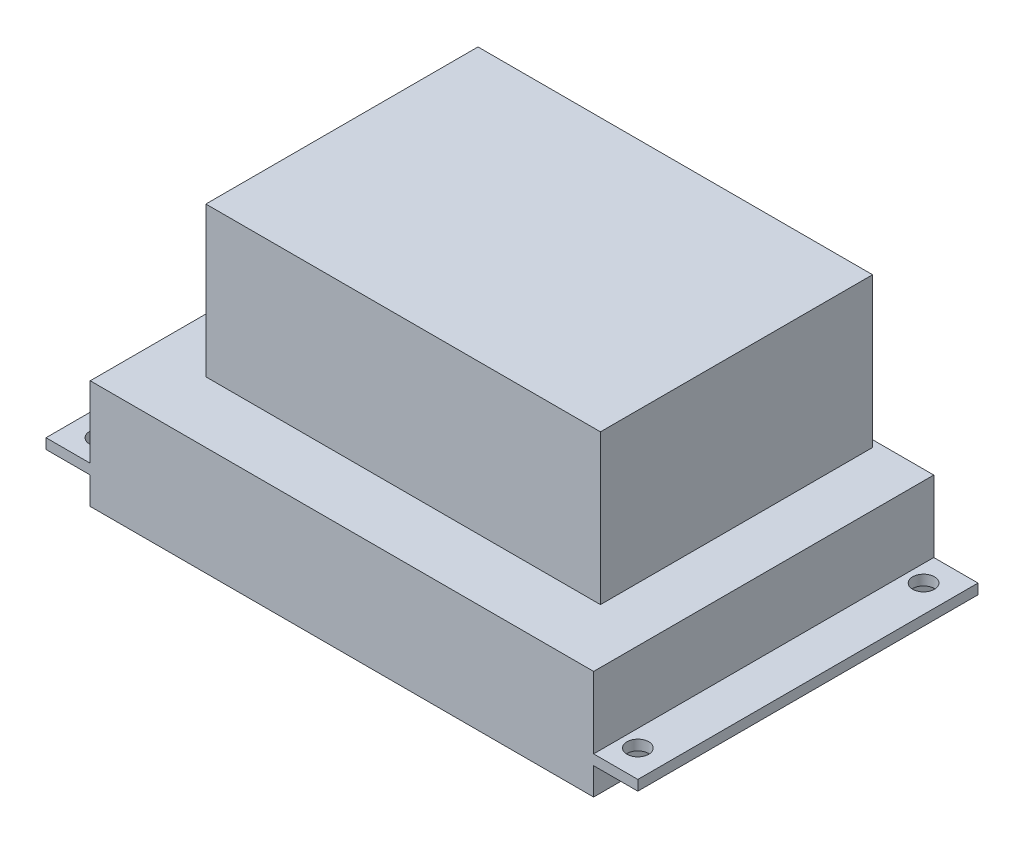
SolidWorks part; units mm, degrees
ref_plane "前视基准面" through (0, 0, 0) normal (0, 0, 1) x (1, 0, 0)
ref_plane "上视基准面" through (0, 0, 0) normal (0, 1, 0) x (1, 0, 0)
ref_plane "右视基准面" through (0, 0, 0) normal (1, 0, 0) x (0, 0, -1)
other "Configuration Table"
sketch "草图1" plane through (0, 0, 0) normal (0, 1, 0) x (1, 0, 0)
  line L0 (-1000, 0) -> (49000, 0) construction
  line L1 (-43.5, -25) -> (43.5, -25)
  line L2 (-43.5, -25) -> (-43.5, 25)
  line L3 (-43.5, 25) -> (43.5, 25)
  line L4 (43.5, -25) -> (43.5, 25)
  line L5 (-43.5, -25) -> (43.5, 25) construction
  line L6 (-43.5, 25) -> (43.5, -25) construction
  line L7 (0, -1000) -> (0, 49000) construction
  circle A0 centre (-39.5, 21) radius 1.6
  circle A1 centre (-39.5, -21) radius 1.6
  circle A2 centre (39.5, -21) radius 1.6
  circle A3 centre (39.5, 21) radius 1.6
  point P0 (0, 0)
  dimension "D3" = 3.2
  dimension "D4" = 4
  dimension "D5" = 4
  dimension "D1" = 87
  dimension "D2" = 50
extrude "凸台-拉伸1" add sketch "草图1" along normal blind 1.5
sketch "草图2" plane through (0, 0, 0) normal (0, -1, 0) x (1, 0, 0)
  line L1 (-37, -25) -> (37, -25)
  line L2 (-37, -25) -> (-37, 25)
  line L3 (-37, 25) -> (37, 25)
  line L4 (37, -25) -> (37, 25)
  line L5 (-37, -25) -> (37, 25) construction
  line L6 (-37, 25) -> (37, -25) construction
  point P0 (0, 0)
  dimension "D1" = 74
  dimension "D2" = 50
extrude "凸台-拉伸2" add sketch "草图2" along normal blind 4 and the other way blind 12
sketch "草图3" plane through (0, 12, 0) normal (0, 1, 0) x (1, 0, 0)
  line L0 (-37, 25) -> (37, 25) construction
  line L1 (-29, 24) -> (29, 24)
  line L2 (-29, 24) -> (-29, -16)
  line L3 (-29, -16) -> (29, -16)
  line L4 (29, 24) -> (29, -16)
  dimension "D1" = 58
  dimension "D2" = 40
  dimension "D3" = 1
  dimension "D4" = 29
extrude "凸台-拉伸3" add sketch "草图3" along normal blind 22
